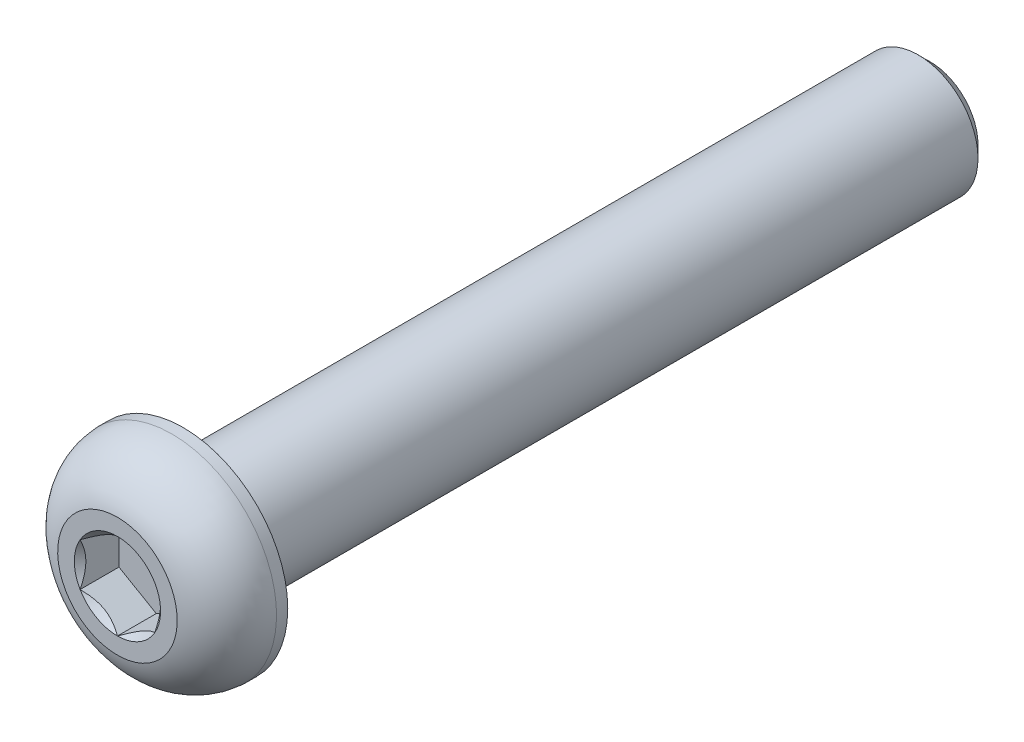
SolidWorks part; units mm, degrees
ref_plane "Front Plane" through (0, 0, 0) normal (0, 0, 1) x (1, 0, 0)
ref_plane "Top Plane" through (0, 0, 0) normal (0, 1, 0) x (1, 0, 0)
ref_plane "Right Plane" through (0, 0, 0) normal (1, 0, 0) x (0, 0, -1)
sketch "Sketch1" plane through (0, 0, 0) normal (0, 0, 1) x (1, 0, 0)
  circle A0 centre (-20, 0) radius 4
  dimension "D1" = 8
  dimension "D2" = 20
extrude "Boss-Extrude1" add sketch "Sketch1" against normal blind 50 from offset 21.2 offset against normal yes
sketch "Sketch2" plane through (0, 0, -21.2) normal (0, 0, 1) x (1, 0, 0)
  circle A0 centre (-20, 0) radius 7
  dimension "D1" = 14
extrude "Boss-Extrude2" add sketch "Sketch2" along normal blind 4.4
ref_plane "Plane1" through (-20, 0, 0) normal (1, 0, 0) x (0, 0, -1)
sketch "Sketch3" plane through (-20, 0, 0) normal (1, 0, 0) x (0, 0, -1)
  line L0 (21.2, 7) -> (16.8, 7) construction
  line L1 (16.8, 7) -> (16.8, -7) construction
  line L2 (16.8, 4) -> (15.8, 4)
  line L3 (15.8, 4) -> (15.8, 8)
  line L4 (15.8, 8) -> (20.9, 8)
  line L5 (20.9, 8) -> (20.9, 7)
  line L6 (21.2, -7) -> (21.2, 7) construction
  line L7 (71.2, 0) -> (16.8, 0) construction
  line L8 (71.2, -4) -> (71.2, 4) construction
  arc A0 (20.9, 7) -> (16.8, 4) centre (20.6746, 3.0064) ccw
  dimension "D5" = 4
  dimension "D1" = 0.3
  dimension "D2" = 1
  dimension "D3" = 4
  dimension "D4" = 1
revolve "Cut-Revolve1" cut sketch "Sketch3" angle 360 about L7
sketch "Sketch4" plane through (0, 0, -16.8) normal (0, 0, 1) x (1, 0, 0)
  line L1 (-20, 2.8868) -> (-22.5, 1.4434)
  line L2 (-22.5, 1.4434) -> (-22.5, -1.4434)
  line L3 (-22.5, -1.4434) -> (-20, -2.8868)
  line L4 (-20, -2.8868) -> (-17.5, -1.4434)
  line L5 (-17.5, -1.4434) -> (-17.5, 1.4434)
  line L6 (-17.5, 1.4434) -> (-20, 2.8868)
  circle A0 centre (-20, 0) radius 2.5 construction
  dimension "D1" = 5
extrude "Cut-Extrude1" cut sketch "Sketch4" against normal blind 2.6
sketch "Sketch5" plane through (0, 0, -16.8) normal (0, 0, 1) x (1, 0, 0)
  circle A0 centre (-20, 0) radius 2.8868
extrude "Cut-Extrude2" cut sketch "Sketch5" against normal blind 1 draft 45
chamfer "Chamfer1" distance 0.8 angle 45 1 edges at (-16, 0, -71.2)
